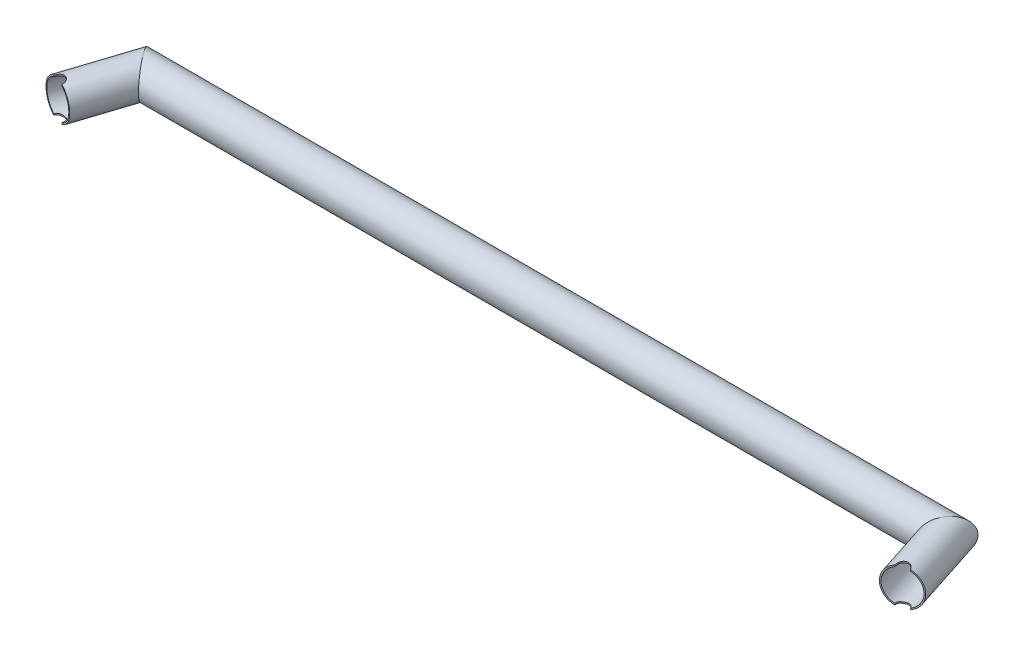
SolidWorks part; units mm, degrees
ref_plane "Front Plane" through (0, 0, 0) normal (0, 0, 1) x (1, 0, 0)
ref_plane "Top Plane" through (0, 0, 0) normal (0, 1, 0) x (1, 0, 0)
ref_plane "Right Plane" through (0, 0, 0) normal (1, 0, 0) x (0, 0, -1)
sketch "Sketch1" plane through (0, 0, 0) normal (0, 1, 0) x (1, 0, 0)
  line L0 (-228.827, 0) -> (228.827, 0)
  line L1 (-228.827, 0) -> (-240.81, -36.88)
  line L2 (228.827, 0) -> (240.81, -36.88)
  point P4 (0, 0)
  dimension "D1" = 481.62
  dimension "D2" = 36.88
  dimension "D3" = 72
  dimension "D4" = 72
ref_plane "Plane4" through (-240.81, 0, 36.88) normal (-0.309, 0, 0.9511) x (0.9511, 0, 0.309)
sketch "Sketch2" plane through (-240.81, 0, 36.88) normal (-0.309, 0, 0.9511) x (0.9511, 0, 0.309)
  line L0 (0, 0) -> (435.2547, 0) construction
  circle A0 centre (0, 0) radius 10.5
  circle A1 centre (0, 0) radius 9.75
  dimension "D1" = 0.75
sweep "Sweep1" add profiles "Sketch2" path "Sketch1"
sketch "Sketch3" plane through (0, 0, 0) normal (0, 1, 0) x (1, 0, 0)
  line L0 (230.8239, -40.1247) -> (250.7961, -33.6353) construction
  line L1 (0, 0) -> (0, -79.8419) construction
  circle A0 centre (240.81, -36.88) radius 3.5
  circle A1 centre (-240.81, -36.88) radius 3.5
  dimension "D1" = 7
extrude "Cut-Extrude1" cut sketch "Sketch3" against normal through all and the other way through all
